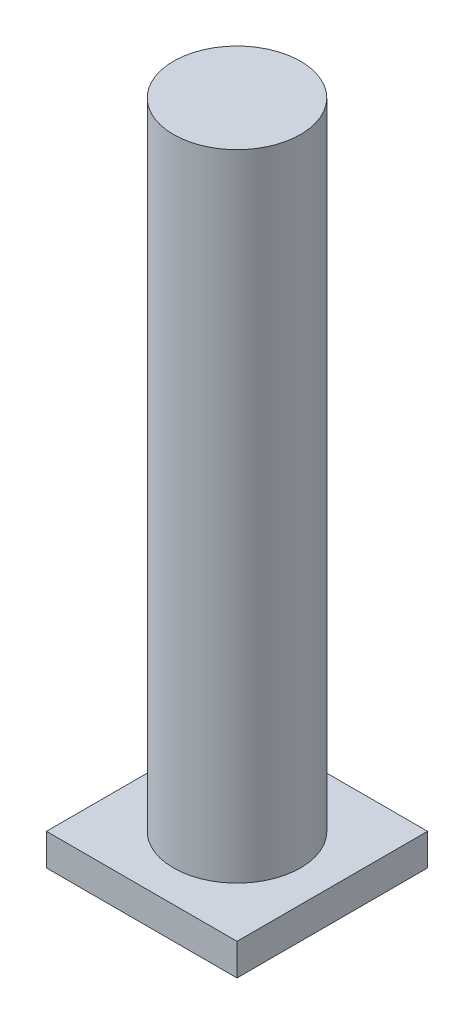
SolidWorks part; units mm, degrees
ref_plane "Front Plane" through (0, 0, 0) normal (0, 0, 1) x (1, 0, 0)
ref_plane "Top Plane" through (0, 0, 0) normal (0, 1, 0) x (1, 0, 0)
ref_plane "Right Plane" through (0, 0, 0) normal (1, 0, 0) x (0, 0, -1)
sketch "Sketch1" plane through (0, 0, 0) normal (0, 1, 0) x (1, 0, 0)
  line L1 (15, -15) -> (-15, -15)
  line L2 (15, -15) -> (15, 15)
  line L3 (15, 15) -> (-15, 15)
  line L4 (-15, -15) -> (-15, 15)
  line L5 (15, -15) -> (-15, 15) construction
  line L6 (15, 15) -> (-15, -15) construction
  point P0 (0, 0)
  dimension "D1" = 30
  dimension "D2" = 30
extrude "Boss-Extrude1" add sketch "Sketch1" along normal blind 5
sketch "Sketch2" plane through (0, 5, 0) normal (0, 1, 0) x (1, 0, 0)
  circle A0 centre (0, 0) radius 10
  dimension "D1" = 20
extrude "Boss-Extrude2" add sketch "Sketch2" along normal blind 100
equation "\"Diameter\" = 20"
equation "\"Length\"= 100"
equation "\"D1@Sketch2\"= \"Diameter\""
equation "\"D1@Boss-Extrude2\"= \"Length\""
